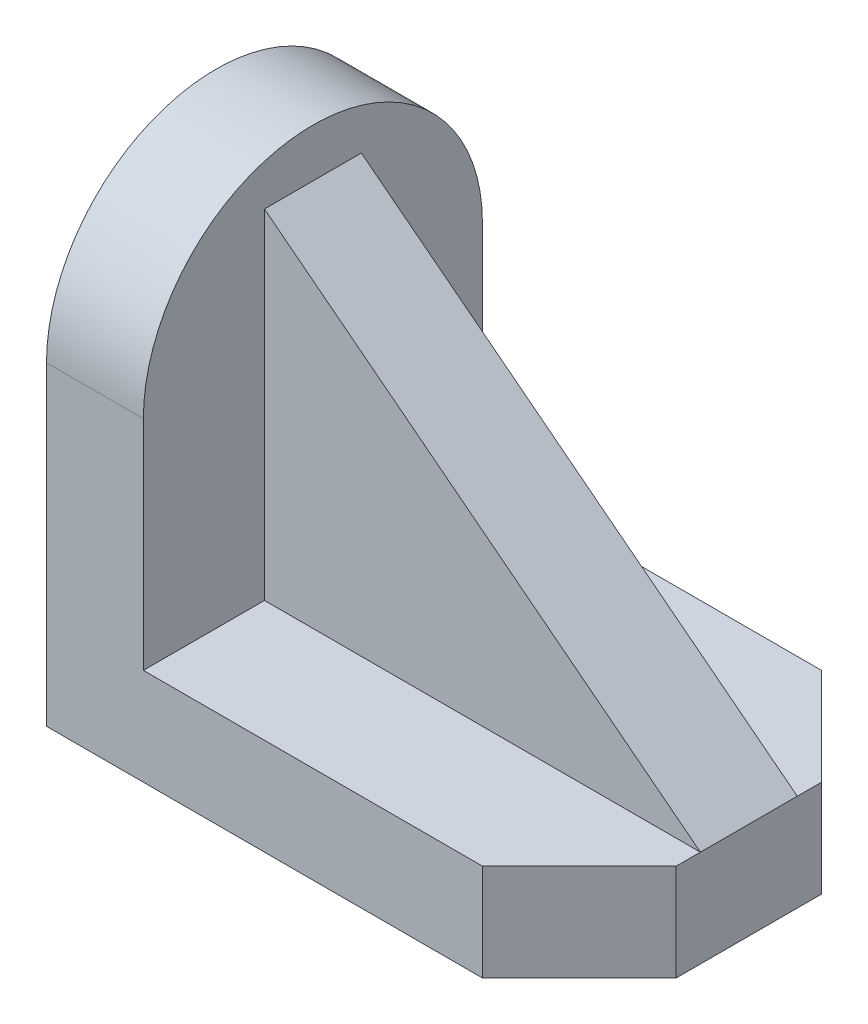
SolidWorks part; units mm, degrees
ref_plane "Front Plane" through (0, 0, 0) normal (0, 0, 1) x (1, 0, 0)
ref_plane "Top Plane" through (0, 0, 0) normal (0, 1, 0) x (1, 0, 0)
ref_plane "Right Plane" through (0, 0, 0) normal (1, 0, 0) x (0, 0, -1)
sketch "Sketch1" plane through (0, 0, 0) normal (0, 1, 0) x (1, 0, 0)
  line L1 (-33, 21) -> (33, 21)
  line L2 (-33, 21) -> (-33, -21)
  line L3 (-33, -21) -> (33, -21)
  line L4 (33, 21) -> (33, -21)
  line L5 (-33, 21) -> (33, -21) construction
  line L6 (-33, -21) -> (33, 21) construction
  point P0 (0, 0)
  dimension "D1" = 66
  dimension "D2" = 42
extrude "Boss-Extrude1" add sketch "Sketch1" along normal blind 12
chamfer "Chamfer1" distance 12 angle 45 1 edges at (33, 6, 21)
chamfer "Chamfer2" distance 12 angle 45 1 edges at (33, 6, -21)
sketch "Sketch2" plane through (-33, 0, 0) normal (-1, 0, 0) x (0, 0, 1)
  line L0 (-21, 12) -> (-21, 39)
  line L1 (21, 12) -> (21, 39)
  line L2 (-21, 12) -> (-21, 0) construction
  line L3 (21, 12) -> (21, 0) construction
  line L4 (-21, 12) -> (21, 12)
  arc A0 (21, 39) -> (-21, 39) centre (0, 39) ccw
  dimension "D1" = 27
  dimension "D2" = 27
extrude "Boss-Extrude2" add sketch "Sketch2" against normal blind 12
sketch "Sketch8" plane through (-33, 0, 0) normal (-1, 0, 0) x (0, 0, 1)
  line L0 (0, 0) -> (0, 54)
  point P3 (0, 0)
  dimension "D1" = 54
sketch "Sketch11" plane through (0, 0, 0) normal (0, 0, 1) x (1, 0, 0)
  line L0 (-21, 54) -> (-21, 12)
  line L1 (-21, 39) -> (-21, 60) construction
  line L2 (-21, 12) -> (33, 12)
  line L3 (33, 12) -> (-21, 54)
  line L4 (33, 12) -> (33, 0) construction
  point P5 (0, 0)
  point P8 (0, 0)
  dimension "D1" = 42
extrude "Boss-Extrude3" add sketch "Sketch11" along normal blind 6 and the other way blind 6
